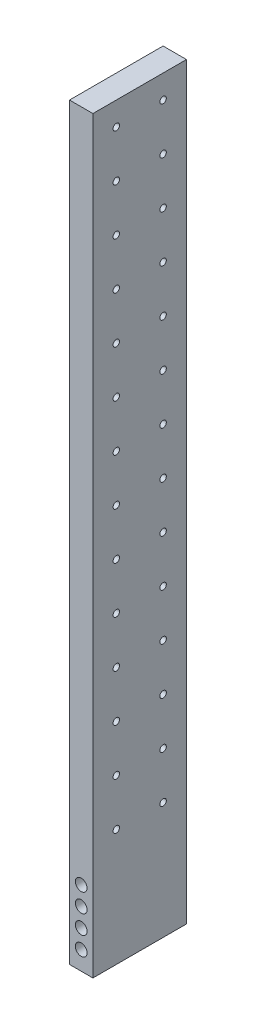
SolidWorks part; units mm, degrees
material "6061 Alloy"
ref_plane "Front" through (0, 0, 0) normal (0, 0, 1) x (1, 0, 0)
ref_plane "Top" through (0, 0, 0) normal (0, 1, 0) x (1, 0, 0)
ref_plane "Right" through (0, 0, 0) normal (1, 0, 0) x (0, 0, -1)
sketch "Sketch1" plane through (0, 0, 0) normal (0, 0, 1) x (1, 0, 0)
  line L0 (0, 0) -> (0, -406.4)
  line L1 (0, -406.4) -> (12.7, -406.4)
  line L4 (12.7, -406.4) -> (12.7, 0)
  line L9 (12.7, 0) -> (0, 0)
  line L10 (12.7, -203.2) -> (0, -203.2) construction
  dimension "D1" = 406.4
  dimension "D4" = 12.7
extrude "Boss-Extrude1" add sketch "Sketch1" along normal mid plane 50.8
hole_wizard "#10-32 Threaded Holes" positions "Sketch10" profile "Sketch9" hole size "#97" standard "ANSI Inch" end condition up to next
sketch "Sketch10" plane through (12.7, 0, 0) normal (1, 0, 0) x (0, 0, -1)
  line L0 (0, 0) -> (0, -406.4) construction
  line L2 (-25.4, -406.4) -> (25.4, -406.4) construction
  line L4 (-12.7, 0) -> (-12.7, -406.4) construction
  line L6 (12.7, 0) -> (12.7, -406.4) construction
  line L8 (-25.4, 0) -> (25.4, 0) construction
  point P0 (-12.7, -12.7)
  point P3 (12.7, -12.7)
  point P50 (-12.7, -38.1)
  point P51 (12.7, -38.1)
  point P52 (-12.7, -63.5)
  point P53 (12.7, -63.5)
  point P54 (-12.7, -88.9)
  point P55 (12.7, -88.9)
  point P56 (-12.7, -114.3)
  point P57 (12.7, -114.3)
  point P58 (-12.7, -139.7)
  point P59 (12.7, -139.7)
  point P60 (-12.7, -165.1)
  point P61 (12.7, -165.1)
  point P62 (-12.7, -190.5)
  point P63 (12.7, -190.5)
  point P64 (-12.7, -215.9)
  point P65 (12.7, -215.9)
  point P66 (-12.7, -241.3)
  point P67 (12.7, -241.3)
  point P68 (-12.7, -266.7)
  point P69 (12.7, -266.7)
  point P70 (-12.7, -292.1)
  point P71 (12.7, -292.1)
  point P72 (-12.7, -317.5)
  point P73 (12.7, -317.5)
  point P74 (-12.7, -342.9)
  point P75 (12.7, -342.9)
  dimension "D1" = 12.7
  dimension "D2" = 12.7
  dimension "D3" = 12.7
  dimension "D4" = 14
  dimension "D5" = 25.4
sketch "Sketch9" plane through (12.7, -12.7, 12.7) normal (0, 1, 0) x (0, 0, -1)
  line L0 (0, 0) -> (0, 12.7)
  line L1 (0, 12.7) -> (1.7551, 12.7)
  line L2 (1.7551, 12.7) -> (1.7551, 0)
  line L5 (1.7551, 0) -> (0, 0)
  line L11 (0, -6.35) -> (0, 107.95) construction
  dimension "Thru Hole Dia." = 3.5103
  dimension "Thru Hole Depth" = 12.7
hole_wizard "CBORE for #10 Hex Machine Screw1" positions "Sketch12" profile "Sketch11" counterbore size "#10" standard "ANSI Inch"
sketch "Sketch12" plane through (0, 0, -25.4) normal (0, 0, -1) x (-1, 0, 0)
  line L0 (-6.35, 0) -> (-6.35, -406.4) construction
  line L1 (-12.7, 0) -> (0, 0) construction
  line L2 (0, -406.4) -> (-12.7, -406.4) construction
  point P0 (-6.35, -396.24)
  point P2 (-6.35, -386.08)
  point P4 (-6.35, -375.92)
  point P6 (-6.35, -365.76)
  dimension "D1" = 10.16
  dimension "D2" = 10.16
  dimension "D3" = 10.16
  dimension "D4" = 10.16
sketch "Sketch11" plane through (6.35, -396.24, -25.4) normal (1, 0, 0) x (0, 1, 0)
  line L0 (0, 0) -> (0, 50.8)
  line L1 (0, 50.8) -> (3.175, 50.8)
  line L2 (3.175, 50.8) -> (3.175, 12.7)
  line L3 (3.175, 12.7) -> (4.7625, 12.7)
  line L4 (4.7625, 12.7) -> (4.7625, 0)
  line L5 (4.7625, 0) -> (0, 0)
  line L10 (0, 50.8) -> (-3.175, 50.8) construction
  line L11 (0, -6.35) -> (0, 107.95) construction
  dimension "Hole Dia." = 6.35
  dimension "Hole Depth" = 50.8
  dimension "C'Bore Dia." = 9.525
  dimension "C'Bore Depth" = 12.7
  dimension "Drill Angle" = 180
